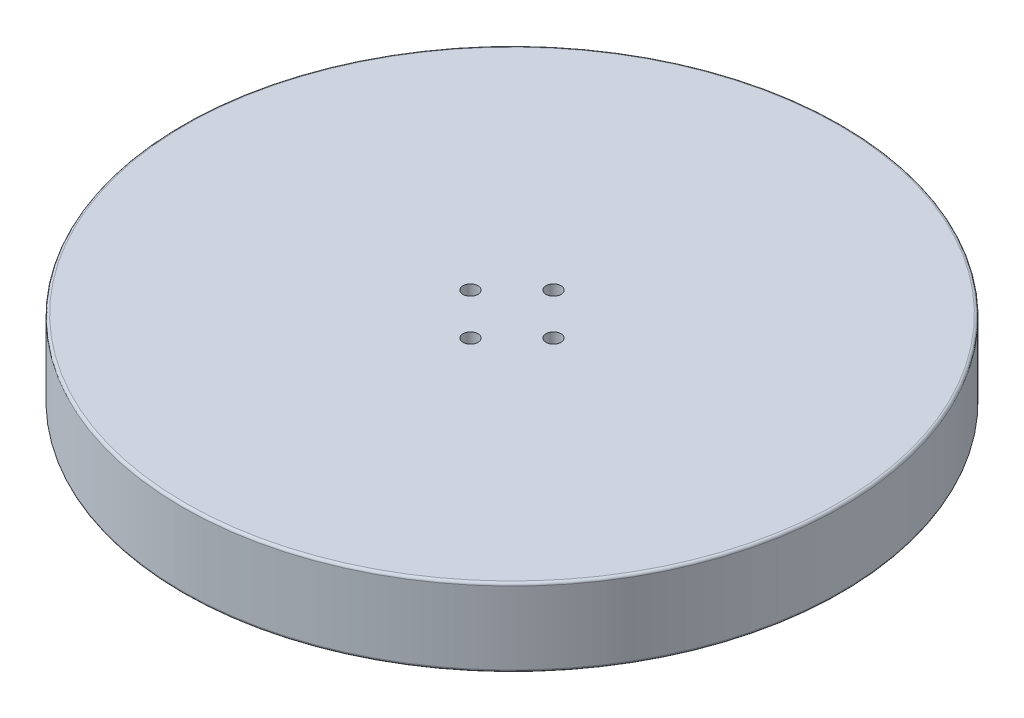
SolidWorks part; units mm, degrees
material "Polyethylene Cross-Linked"
ref_plane "Front Plane" through (0, 0, 0) normal (0, 0, 1) x (1, 0, 0)
ref_plane "Top Plane" through (0, 0, 0) normal (0, 1, 0) x (1, 0, 0)
ref_plane "Right Plane" through (0, 0, 0) normal (1, 0, 0) x (0, 0, -1)
sketch "Sketch2" plane through (0, 0, 0) normal (0, 1, 0) x (1, 0, 0)
  circle A0 centre (0, 0) radius 63.5
  point P3 (0, 0)
  point P13 (0, 0)
  point P19 (0, 0)
  dimension "D1" = 127
extrude "Boss-Extrude1" add sketch "Sketch2" along normal blind 15
sketch "Sketch3" plane through (0, 15, 0) normal (0, 1, 0) x (1, 0, 0)
  circle A0 centre (0, 0) radius 8 construction
  circle A1 centre (0, 8) radius 1.45
  circle A2 centre (8, 0) radius 1.45
  circle A3 centre (0, -8) radius 1.45
  circle A4 centre (-8, 0) radius 1.45
  point P14 (0, 0)
  dimension "D1" = 16
  dimension "D2" = 2.9
  dimension "D3" = 4
extrude "Cut-Extrude1" cut sketch "Sketch3" against normal through all
fillet "Fillet2" radius 0.5 2 edges at (0, 15, 63.5) (0, 0, 63.5)
